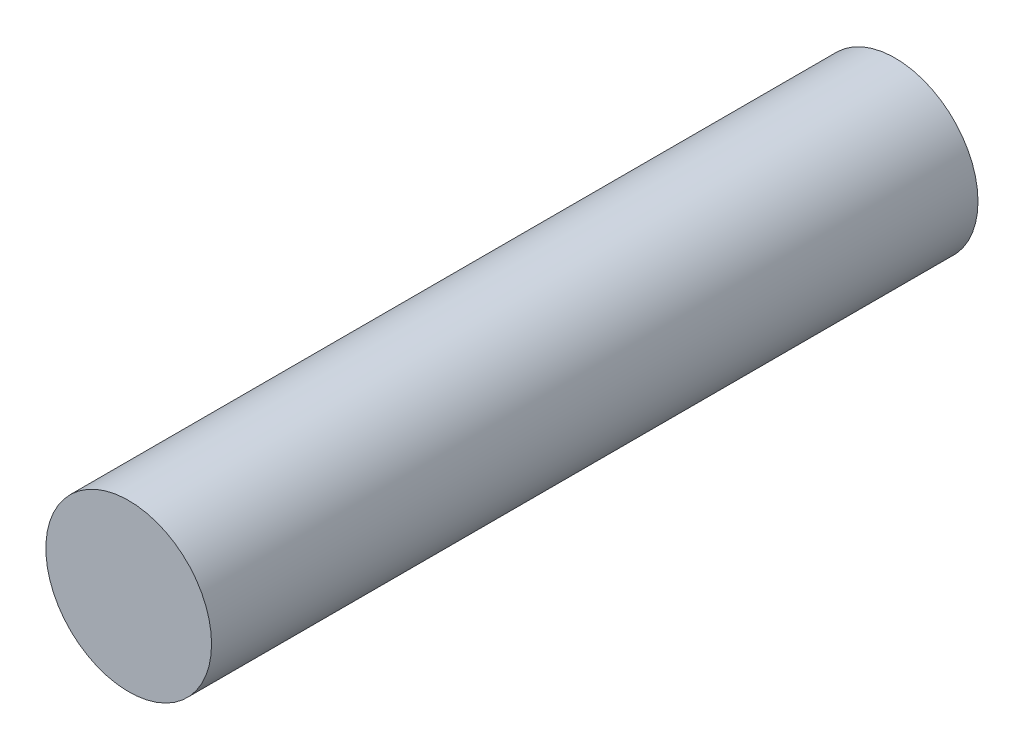
SolidWorks part; units mm, degrees
ref_plane "前视基准面" through (0, 0, 0) normal (0, 0, 1) x (1, 0, 0)
ref_plane "上视基准面" through (0, 0, 0) normal (0, 1, 0) x (1, 0, 0)
ref_plane "右视基准面" through (0, 0, 0) normal (1, 0, 0) x (0, 0, -1)
sketch "草图1" plane through (0, 0, 0) normal (0, 0, 1) x (1, 0, 0)
  circle A0 centre (0, 0) radius 4
extrude "凸台-拉伸1" add sketch "草图1" along normal blind 37 contours A0
